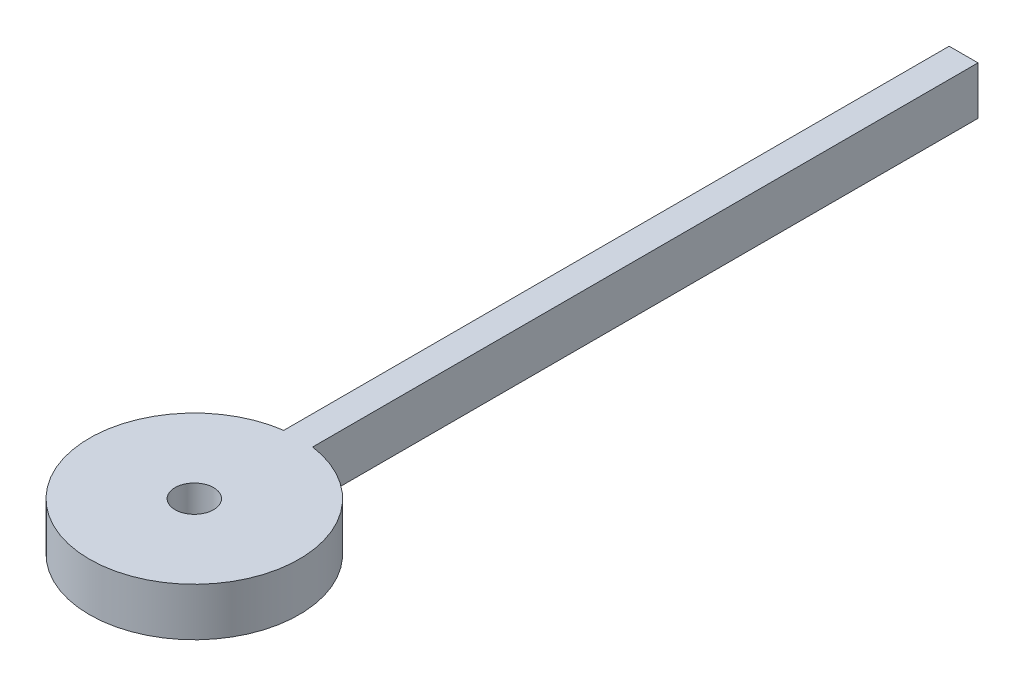
SolidWorks part; units mm, degrees
ref_plane "Front Plane" through (0, 0, 0) normal (0, 0, 1) x (1, 0, 0)
ref_plane "Top Plane" through (0, 0, 0) normal (0, 1, 0) x (1, 0, 0)
ref_plane "Right Plane" through (0, 0, 0) normal (1, 0, 0) x (0, 0, -1)
sketch "Sketch1" plane through (0, 0, 0) normal (0, 1, 0) x (1, 0, 0)
  line L0 (-3, 160) -> (3, 160)
  line L1 (3, 21.6101) -> (3, 160)
  line L2 (-3, 21.6101) -> (-3, 160)
  circle A0 centre (0, 0) radius 4
  arc A1 (-3, 21.6101) -> (3, 21.6101) centre (0, 0) ccw
  dimension "D1" = 160
  dimension "D2" = 21.8173
  dimension "D3" = 8
extrude "Boss-Extrude1" add sketch "Sketch1" along normal blind 10
